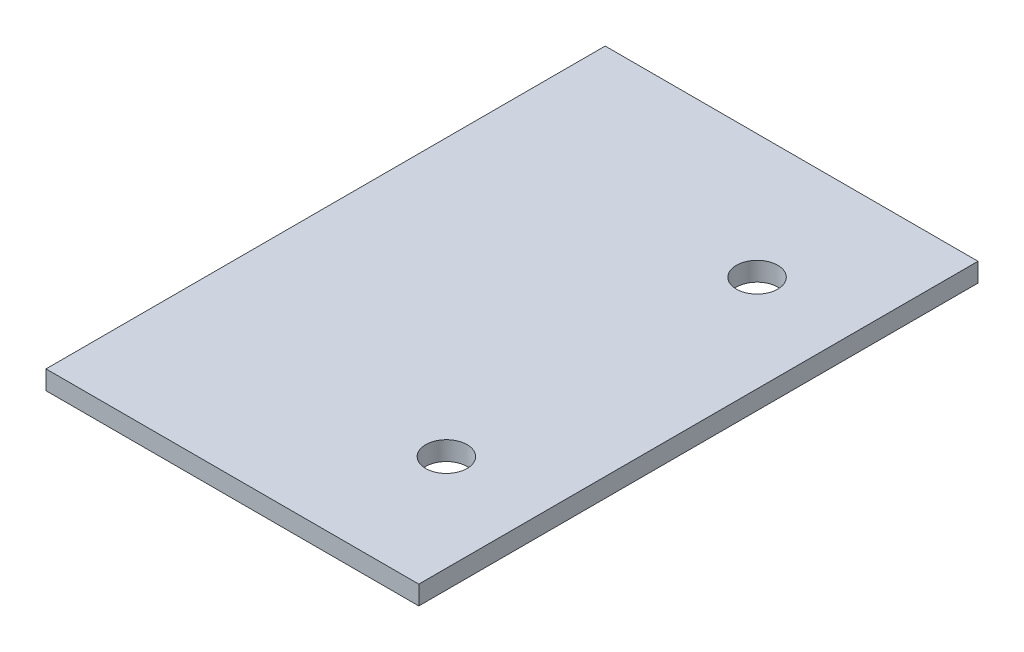
SolidWorks part; units mm, degrees
ref_plane "Front" through (0, 0, 0) normal (0, 0, 1) x (1, 0, 0)
ref_plane "Top" through (0, 0, 0) normal (0, 1, 0) x (1, 0, 0)
ref_plane "Right" through (0, 0, 0) normal (1, 0, 0) x (0, 0, -1)
sketch "Sketch1" plane through (0, 0, 0) normal (0, 1, 0) x (1, 0, 0)
  line L1 (-15, 22.5) -> (15, 22.5)
  line L2 (-15, 22.5) -> (-15, -22.5)
  line L3 (-15, -22.5) -> (15, -22.5)
  line L4 (15, 22.5) -> (15, -22.5)
  line L5 (-15, 22.5) -> (15, -22.5) construction
  line L6 (-15, -22.5) -> (15, 22.5) construction
  point P0 (0, 0)
  dimension "D1" = 30
  dimension "D2" = 45
extrude "Boss-Extrude1" add sketch "Sketch1" along normal blind 1.524
sketch "Sketch2" plane through (0, 1.524, 0) normal (0, 1, 0) x (1, 0, 0)
  line L0 (15, -22.5) -> (15, 22.5) construction
  line L1 (7.2214, -12.5) -> (7.2214, -22.5) construction
  line L2 (-15, -22.5) -> (15, -22.5) construction
  line L3 (7.2214, 12.5) -> (7.2214, 22.5) construction
  line L4 (15, 22.5) -> (-15, 22.5) construction
  line L5 (7.2214, -12.5) -> (7.2214, 12.5) construction
  circle A0 centre (7.2214, 12.5) radius 1.665
  circle A1 centre (7.2214, -12.5) radius 1.665
  dimension "D1" = 3.33
  dimension "D2" = 7.7786
  dimension "D3" = 10
extrude "Cut-Extrude1" cut sketch "Sketch2" against normal up to next
